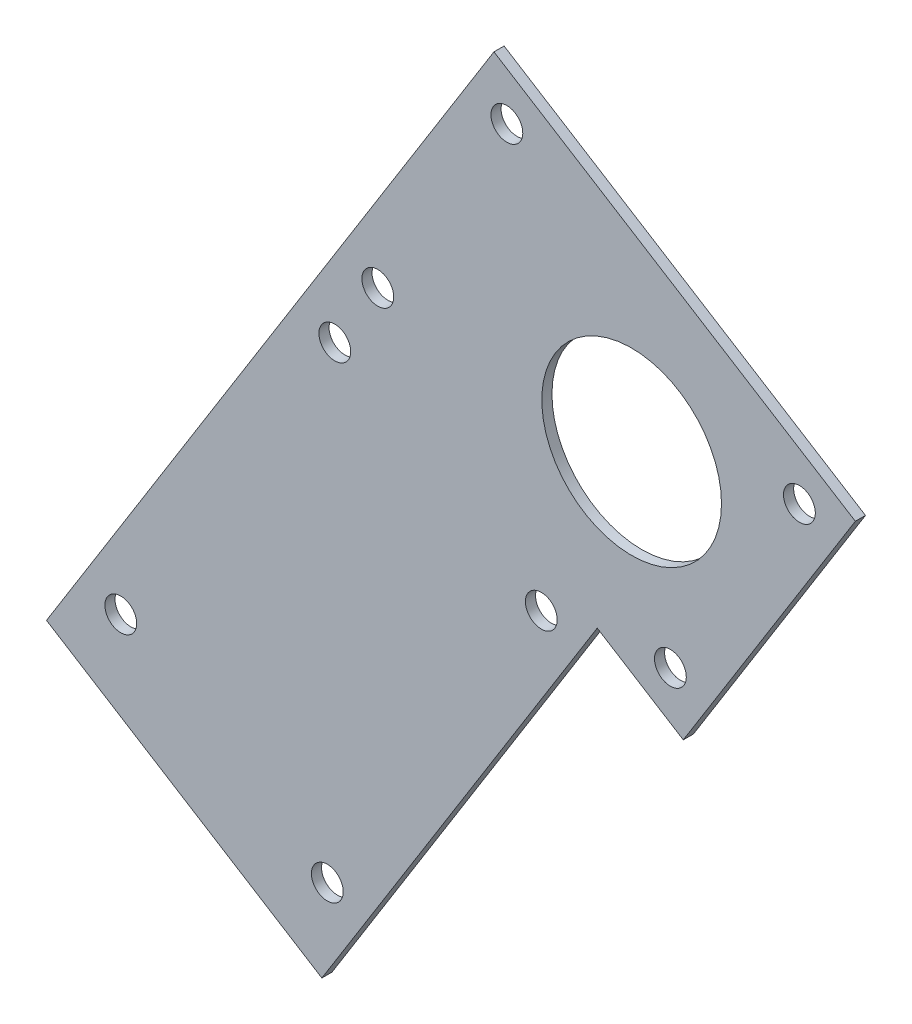
SolidWorks part; units mm, degrees
ref_plane "Front Plane" through (0, 0, 0) normal (0, 0, 1) x (1, 0, 0)
ref_plane "Top Plane" through (0, 0, 0) normal (0, 1, 0) x (1, 0, 0)
ref_plane "Right Plane" through (0, 0, 0) normal (1, 0, 0) x (0, 0, -1)
sketch "Sketch2" plane through (0, 0, 189.79) normal (0, 0, -1) x (-1, 0, 0)
  line L1 (57.8647, -87.4314) -> (84.7846, -130.5123)
  line L2 (84.7846, -130.5123) -> (98.2474, -122.0998)
  line L3 (98.2474, -122.0998) -> (141.3339, -191.0526)
  line L4 (98.2474, -122.0998) -> (266.4968, -391.3551) construction
  line L5 (141.3339, -191.0526) -> (184.4147, -164.1327)
  line L6 (141.3282, -95.1799) -> (309.5776, -364.4352) construction
  line L7 (184.4147, -164.1327) -> (114.4083, -52.0991)
  line L8 (224.803, 16.8832) -> (57.8647, -87.4314) construction
  line L9 (114.4083, -52.0991) -> (57.8647, -87.4314)
extrude "Boss-Extrude1" add sketch "Sketch2" along normal blind 1.5875
hole_wizard "#10 Clearance Hole1" positions "Sketch3" profile "Sketch4" hole size "#10" standard "ANSI Inch" end condition through all
sketch "Sketch3" plane through (0, 0, 188.2025) normal (0, 0, -1) x (-1, 0, 0)
  point P0 (106.9975, -124.1199)
  point P3 (86.8047, -121.7622)
  point P9 (112.3882, -60.8492)
  point P12 (132.5781, -93.1598)
  point P15 (139.3081, -103.93)
  point P18 (172.7921, -157.5156)
  point P21 (140.4815, -177.7055)
  point P24 (0, 0)
sketch "Sketch4" plane through (-106.9975, -124.1199, 188.2025) normal (1, 0, 0) x (0, 1, 0)
  line L0 (0, 0) -> (0, 1.5875)
  line L1 (0, 1.5875) -> (2.4892, 1.5875)
  line L2 (2.4892, 1.5875) -> (2.4892, 0)
  line L5 (2.4892, 0) -> (0, 0)
  line L11 (0, -6.35) -> (0, 107.95) construction
  dimension "Thru Hole Dia." = 4.9784
  dimension "Thru Hole Depth" = 1.5875
sketch "Sketch5" plane through (0, 0, 189.79) normal (0, 0, 1) x (1, 0, 0)
  circle A0 centre (-92.8651, -95.5119) radius 14.0572
extrude "Cut-Extrude1" cut sketch "Sketch5" against normal blind 2.54
hole_wizard "#10 Clearance Hole2" positions "Sketch10" profile "Sketch11" hole size "#10" standard "ANSI Inch" end condition through all
sketch "Sketch10" plane through (0, 0, 189.79) normal (0, 0, 1) x (1, 0, 0)
  point P5 (-66.6148, -89.4516)
sketch "Sketch11" plane through (-66.6148, -89.4516, 189.79) normal (1, 0, 0) x (0, -1, 0)
  line L0 (0, 0) -> (0, 1.5875)
  line L1 (0, 1.5875) -> (2.4892, 1.5875)
  line L2 (2.4892, 1.5875) -> (2.4892, 0)
  line L5 (2.4892, 0) -> (0, 0)
  line L11 (0, -6.35) -> (0, 107.95) construction
  dimension "Thru Hole Dia." = 4.9784
  dimension "Thru Hole Depth" = 1.5875
